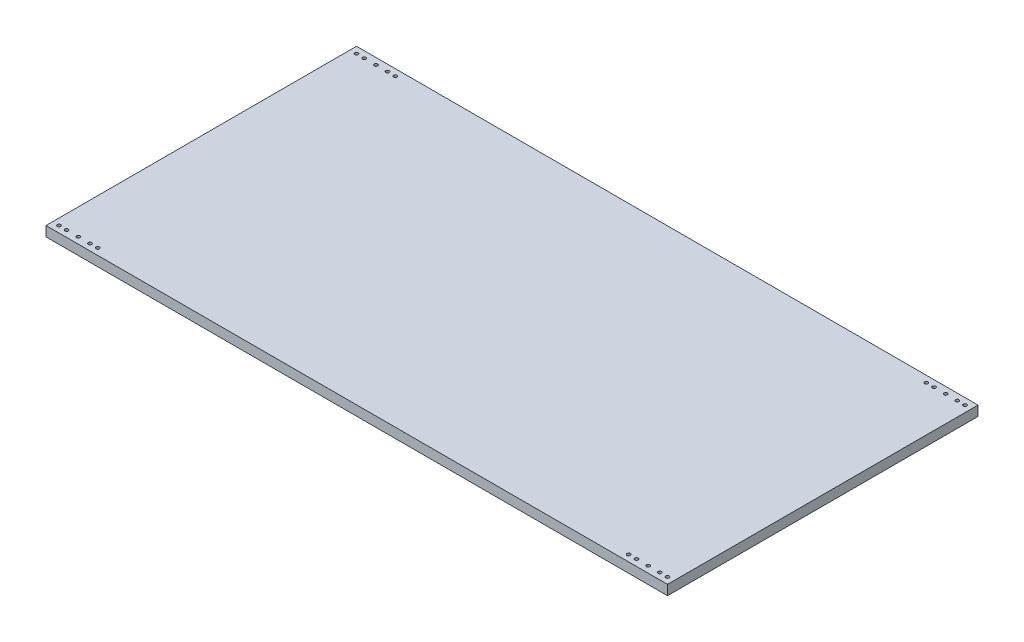
SolidWorks part; units mm, degrees
ref_plane "Front Plane" through (0, 0, 0) normal (0, 0, 1) x (1, 0, 0)
ref_plane "Top Plane" through (0, 0, 0) normal (0, 1, 0) x (1, 0, 0)
ref_plane "Right Plane" through (0, 0, 0) normal (1, 0, 0) x (0, 0, -1)
sketch "Sketch1" plane through (0, 0, 0) normal (0, 1, 0) x (1, 0, 0)
  line L1 (-600.5, 300) -> (600.5, 300)
  line L2 (-600.5, 300) -> (-600.5, -300)
  line L3 (-600.5, -300) -> (600.5, -300)
  line L4 (600.5, 300) -> (600.5, -300)
  line L5 (-600.5, 300) -> (600.5, -300) construction
  line L6 (-600.5, -300) -> (600.5, 300) construction
  point P0 (0, 0)
  dimension "D1" = 1201
  dimension "D2" = 600
extrude "Boss-Extrude1" add sketch "Sketch1" along normal blind 19.05
hole_wizard "M6 Clearance Hole1" positions "Sketch2" profile "Sketch3" hole size "M6" standard "ANSI Metric" end condition through all
sketch "Sketch2" plane through (0, 0, 0) normal (0, -1, 0) x (1, 0, 0)
  point P0 (-588, 287.5)
  point P1 (-573, 287.5)
  point P3 (-550.5, 287.5)
  point P5 (-528, 287.5)
  point P7 (-513, 287.5)
  point P9 (-588, -287.5)
  point P11 (-573, -287.5)
  point P13 (-550.5, -287.5)
  point P15 (-528, -287.5)
  point P17 (-513, -287.5)
  point P19 (513, -287.5)
  point P21 (528, -287.5)
  point P23 (550.5, -287.5)
  point P25 (573, -287.5)
  point P27 (588, -287.5)
  point P29 (513, 287.5)
  point P31 (528, 287.5)
  point P33 (550.5, 287.5)
  point P35 (573, 287.5)
  point P37 (588, 287.5)
sketch "Sketch3" plane through (-588, 0, 287.5) normal (1, 0, 0) x (0, 0, -1)
  line L0 (0, 0) -> (0, 19.05)
  line L1 (0, 19.05) -> (3.3, 19.05)
  line L2 (3.3, 19.05) -> (3.3, 0)
  line L3 (3.3, 0) -> (0, 0)
  line L4 (0, -6.35) -> (0, 107.95) construction
  dimension "Thru Hole Dia." = 6.6
  dimension "Thru Hole Depth" = 19.05
